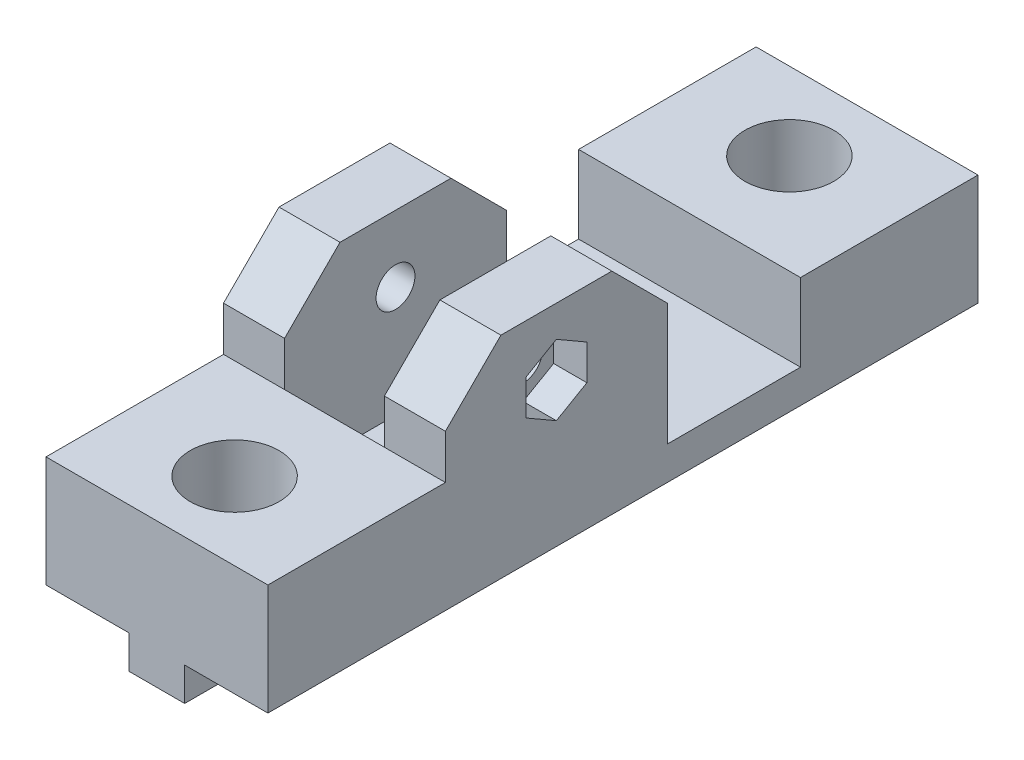
SolidWorks part; units mm, degrees
ref_plane "Front Plane" through (0, 0, 0) normal (0, 0, 1) x (1, 0, 0)
ref_plane "Top Plane" through (0, 0, 0) normal (0, 1, 0) x (1, 0, 0)
ref_plane "Right Plane" through (0, 0, 0) normal (1, 0, 0) x (0, 0, -1)
sketch "Sketch1" plane through (0, 0, 0) normal (0, 1, 0) x (1, 0, 0)
  line L1 (-10, -15) -> (10, -15)
  line L2 (-10, -15) -> (-10, 15)
  line L3 (-10, 15) -> (10, 15)
  line L4 (10, -15) -> (10, 15)
  line L5 (-10, -15) -> (10, 15) construction
  line L6 (-10, 15) -> (10, -15) construction
  point P0 (0, 0)
  dimension "D1" = 20
  dimension "D2" = 30
extrude "Boss-Extrude1" add sketch "Sketch1" along normal blind 3
sketch "Sketch2" plane through (0, 0, 0) normal (0, -1, 0) x (1, 0, 0)
  line L0 (10, -15) -> (-10, -15) construction
  line L1 (-2.5, -15) -> (2.5, -15)
  line L2 (-2.5, -15) -> (-2.5, -3)
  line L3 (-2.5, -3) -> (2.5, -3)
  line L4 (2.5, -15) -> (2.5, -3)
  line L5 (-2.5, -15) -> (2.5, -3) construction
  line L6 (-2.5, -3) -> (2.5, -15) construction
  point P0 (0, -9)
  dimension "D1" = 0
  dimension "D2" = 5
  dimension "D3" = 0
  dimension "D4" = 12
extrude "Boss-Extrude2" add sketch "Sketch2" along normal blind 3
sketch "Sketch3" plane through (0, 3, 0) normal (0, 1, 0) x (1, 0, 0)
  line L0 (10, 15) -> (-10, 15) construction
  circle A0 centre (0, 8) radius 4
  circle A1 centre (0, 8) radius 7
  dimension "D1" = 14
  dimension "D2" = 7
  dimension "D3" = 8
extrude "Boss-Extrude3" add sketch "Sketch3" along normal blind 7
sketch "Sketch4" plane through (0, 3, 0) normal (0, 1, 0) x (1, 0, 0)
  circle A1 centre (0, 8) radius 4
  circle A2 centre (0, 8) radius 4
  dimension "D1" = 0
extrude "Boss-Extrude4" add sketch "Sketch4" along normal blind 1
sketch "Sketch5" plane through (0, 3, 0) normal (0, 1, 0) x (1, 0, 0)
  line L0 (-10, -15) -> (10, -15) construction
  circle A0 centre (0, -8.5) radius 3
  point P4 (0, 0)
  point P7 (-0.7919, -3)
  dimension "D1" = 6
  dimension "D2" = 6.5
  dimension "D3" = 0
extrude "Cut-Extrude1" cut sketch "Sketch5" against normal through all both and the other way through all
chamfer "Chamfer1" [suppressed] distance 4 angle 45
sketch "Sketch6" plane through (0, 3, 0) normal (0, 1, 0) x (1, 0, 0)
  line L0 (10, -15) -> (10, 15) construction
  line L1 (-10, 15) -> (10, 15)
  line L2 (-10, 15) -> (-10, -1)
  line L3 (-10, -1) -> (10, -1)
  line L4 (10, 15) -> (10, -1)
  circle A0 centre (0, 8) radius 7 construction
  circle A1 centre (0, 8) radius 7
  circle A3 centre (0, 8) radius 4
  circle A4 centre (0, 8) radius 4
  line M6 (10, 15) -> (0, 15)
  circle M7 centre (0, 8) radius 7
  line M8 (0, 15) -> (-10, 15)
  line M9 (-10, 15) -> (-10, -15)
  line M11 (10, -15) -> (10, 15)
  dimension "D1" = 16
  dimension "D2" = 0
extrude "Boss-Extrude6" add sketch "Sketch6" along normal up to surface (7 mm away) contours A4 M7 | L3 M9 M11 M6 M7 M8 up to face at (0, 10, -1)
ref_plane "Plane1" through (0, 0, -8) normal (0, 0, 1) x (1, 0, 0)
ref_plane "Plane2" through (0, 0, 17) normal (0, 0, 1) x (1, 0, 0)
sketch "Sketch7" plane through (0, 0, 15) normal (0, 0, 1) x (1, 0, 0)
  line L4 (-10, 0) -> (10, 0)
  line L5 (10, 0) -> (10, 3)
  line L6 (10, 3) -> (-10, 3)
  line L7 (-10, 3) -> (-10, 0)
  line L8 (-10, 0) -> (10, 0)
  line L9 (10, 0) -> (10, 3)
  line L10 (10, 3) -> (-10, 3)
  line L11 (-10, 3) -> (-10, 0)
  dimension "D1" = 0
extrude "Boss-Extrude7" add sketch "Sketch7" along normal blind 19
mirror "Mirror3" about plane through (0, 0, 17) normal (0, 0, 1) of "Boss-Extrude6", "Boss-Extrude4", "Boss-Extrude3", "Boss-Extrude2", "Boss-Extrude1"
sketch "Sketch8" plane through (0, 0, 37) normal (0, 0, -1) x (-1, 0, 0)
  line L4 (2.5, 0) -> (-2.5, 0)
  line L5 (-2.5, 0) -> (-2.5, -3)
  line L6 (-2.5, -3) -> (2.5, -3)
  line L7 (2.5, -3) -> (2.5, 0)
  line L8 (2.5, 0) -> (-2.5, 0)
  line L9 (-2.5, 0) -> (-2.5, -3)
  line L10 (-2.5, -3) -> (2.5, -3)
  line L11 (2.5, -3) -> (2.5, 0)
  dimension "D1" = 0
extrude "Boss-Extrude8" add sketch "Sketch8" along normal blind 12
sketch "Sketch10" plane through (0, 3, 0) normal (0, 1, 0) x (1, 0, 0)
  line L0 (-10, -33) -> (10, -33) construction
  line L1 (4.5, -13) -> (-4.5, -13)
  line L2 (4.5, -13) -> (4.5, -33)
  line L3 (4.5, -33) -> (-4.5, -33)
  line L4 (-4.5, -13) -> (-4.5, -33)
  line L5 (4.5, -13) -> (-4.5, -33) construction
  line L6 (4.5, -33) -> (-4.5, -13) construction
  line L8 (-10, -1) -> (-10, -33) construction
  line L9 (-4.5, -13) -> (-10, -13)
  line L10 (-4.5, -13) -> (-4.5, -33)
  line L11 (-4.5, -33) -> (-10, -33)
  line L12 (-10, -13) -> (-10, -33)
  line L14 (4.5, -13) -> (10, -13)
  line L15 (4.5, -13) -> (4.5, -33)
  line L16 (4.5, -33) -> (10, -33)
  line L17 (10, -13) -> (10, -33)
  circle A0 centre (0, -8.5) radius 3 construction
  circle A1 centre (0, -8.5) radius 3
  circle A2 centre (0, -8.5) radius 6
  point P0 (0, -23)
  line M15 (-10, -1) -> (-10, -33)
  line M16 (-10, -33) -> (10, -33)
  line M17 (10, -33) -> (10, -1)
  dimension "D4" = 12
  dimension "D1" = 0
  dimension "D2" = 20
  dimension "D3" = 9
extrude "Boss-Extrude9" add sketch "Sketch10" along normal blind 16 contours L4 L9 M15 M16 | L14 L2 M16 M17
sketch "Sketch11" plane through (-10, 0, 0) normal (-1, 0, 0) x (0, 0, 1)
  line L0 (17, -11) -> (17, 11) construction
  circle A0 centre (23, 13) radius 1.75
  dimension "D3" = 3.5
  dimension "D1" = 6
  dimension "D2" = 10
extrude "Cut-Extrude2" cut sketch "Sketch11" against normal through all both and the other way through all
sketch "Sketch12" plane through (-10, 0, 0) normal (-1, 0, 0) x (0, 0, 1)
  circle A0 centre (23, 13) radius 1.75 construction
  circle A1 centre (23, 13) radius 1.75
  circle A2 centre (23, 13) radius 3
  dimension "D1" = 6
extrude "Cut-Extrude3" cut sketch "Sketch12" against normal blind 3
sketch "Sketch13" plane through (10, 0, 0) normal (1, 0, 0) x (0, 0, -1)
  line L1 (-23, 16.1754) -> (-25.75, 14.5877)
  line L2 (-25.75, 14.5877) -> (-25.75, 11.4123)
  line L3 (-25.75, 11.4123) -> (-23, 9.8246)
  line L4 (-23, 9.8246) -> (-20.25, 11.4123)
  line L5 (-20.25, 11.4123) -> (-20.25, 14.5877)
  line L6 (-20.25, 14.5877) -> (-23, 16.1754)
  circle A0 centre (-23, 13) radius 1.75 construction
  circle A1 centre (-23, 13) radius 1.75
  circle A2 centre (-23, 13) radius 2.75 construction
  dimension "D1" = 5.5
extrude "Cut-Extrude4" cut sketch "Sketch13" against normal blind 3
chamfer "Chamfer2" distance 5 angle 45 4 edges at (7.25, 19, 13) (7.25, 19, 33) (-7.25, 19, 33) (-7.25, 19, 13)
sketch "Sketch14" plane through (0, 4, 0) normal (0, 1, 0) x (1, 0, 0)
  circle A0 centre (0, -42) radius 4 construction
  circle A1 centre (0, 8) radius 4 construction
  circle A2 centre (0, -42) radius 4
  circle A3 centre (0, 8) radius 4
extrude "Cut-Extrude5" cut sketch "Sketch14" against normal blind 1.5
